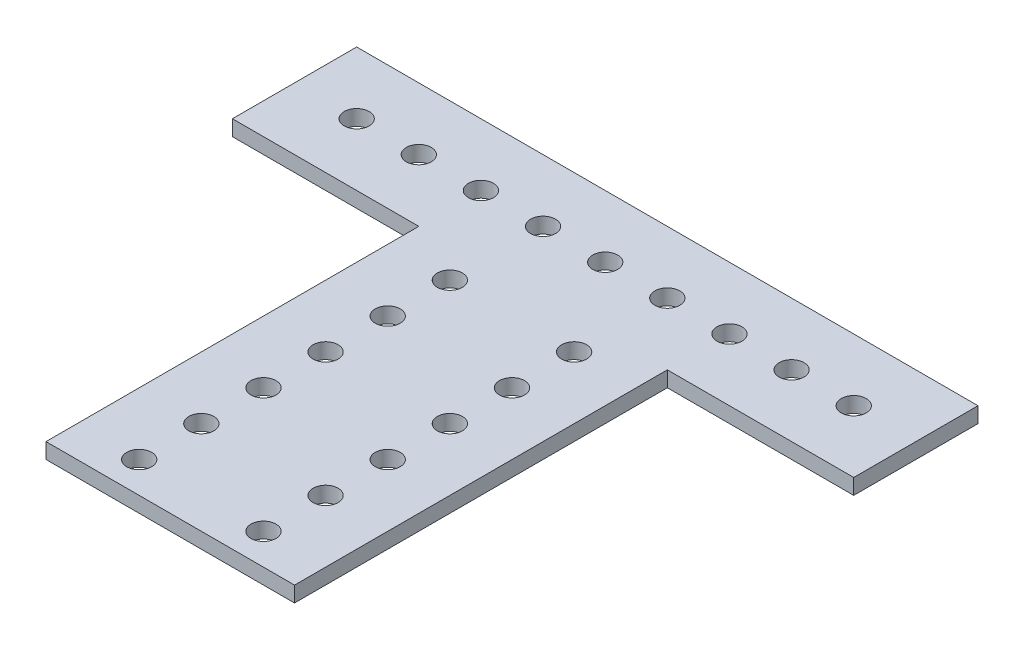
SolidWorks part; units mm, degrees
ref_plane "Front Plane" through (0, 0, 0) normal (0, 0, 1) x (1, 0, 0)
ref_plane "Top Plane" through (0, 0, 0) normal (0, 1, 0) x (1, 0, 0)
ref_plane "Right Plane" through (0, 0, 0) normal (1, 0, 0) x (0, 0, -1)
sketch "Sketch1" plane through (0, 0, 0) normal (0, 1, 0) x (1, 0, 0)
  line L0 (0, 0) -> (50.8, 0)
  line L1 (50.8, 0) -> (50.8, 76.2)
  line L2 (50.8, 76.2) -> (88.9, 76.2)
  line L3 (88.9, 76.2) -> (88.9, 101.6)
  line L4 (88.9, 101.6) -> (-38.1, 101.6)
  line L5 (-38.1, 101.6) -> (-38.1, 76.2)
  line L6 (-38.1, 76.2) -> (0, 76.2)
  line L7 (0, 76.2) -> (0, 0)
  dimension "D1" = 101.6
  dimension "D2" = 76.2
  dimension "D3" = 76.2
  dimension "D4" = 50.8
  dimension "D5" = 127
extrude "Boss-Extrude1" add sketch "Sketch1" along normal blind 3.175
sketch "Sketch2" plane through (0, 3.175, 0) normal (0, 1, 0) x (1, 0, 0)
  line L0 (0, 0) -> (50.8, 0) construction
  line L1 (0, 76.2) -> (0, 0) construction
  line L2 (38.1, 6.35) -> (38.1, 19.05) construction
  circle A0 centre (38.1, 6.35) radius 2.5527
  circle A1 centre (12.7, 6.35) radius 2.5527
  circle A2 centre (38.1, 19.05) radius 2.5527
  circle A3 centre (12.7, 19.05) radius 2.5527
  circle A4 centre (38.1, 31.75) radius 2.5527
  circle A5 centre (12.7, 31.75) radius 2.5527
  circle A6 centre (38.1, 44.45) radius 2.5527
  circle A7 centre (12.7, 44.45) radius 2.5527
  circle A8 centre (38.1, 57.15) radius 2.5527
  circle A9 centre (12.7, 57.15) radius 2.5527
  circle A10 centre (38.1, 69.85) radius 2.5527
  circle A11 centre (12.7, 69.85) radius 2.5527
  dimension "D1" = 6.35
  dimension "D2" = 6.35
  dimension "D3" = 5.1054
  dimension "D4" = 5.1054
  dimension "D5" = 25.4
  dimension "D6" = 12.7
  dimension "D7" = 12.7
extrude "Cut-Extrude1" cut sketch "Sketch2" against normal through all
sketch "Sketch3" plane through (0, 3.175, 0) normal (0, 1, 0) x (1, 0, 0)
  line L0 (88.9, 76.2) -> (88.9, 101.6) construction
  line L1 (273.05, 101.6) -> (-171.45, 101.6) construction
  circle A0 centre (76.2, 88.9) radius 2.5527
  circle A1 centre (63.5, 88.9) radius 2.5527
  circle A2 centre (50.8, 88.9) radius 2.5527
  circle A3 centre (38.1, 88.9) radius 2.5527
  circle A4 centre (25.4, 88.9) radius 2.5527
  circle A5 centre (12.7, 88.9) radius 2.5527
  circle A6 centre (0, 88.9) radius 2.5527
  circle A7 centre (-12.7, 88.9) radius 2.5527
  circle A8 centre (-25.4, 88.9) radius 2.5527
  dimension "D1" = 12.7
  dimension "D2" = 5.1054
  dimension "D3" = 12.7
  dimension "D5" = 12.7
  dimension "D4" = 9
extrude "Cut-Extrude2" cut sketch "Sketch3" against normal through all
